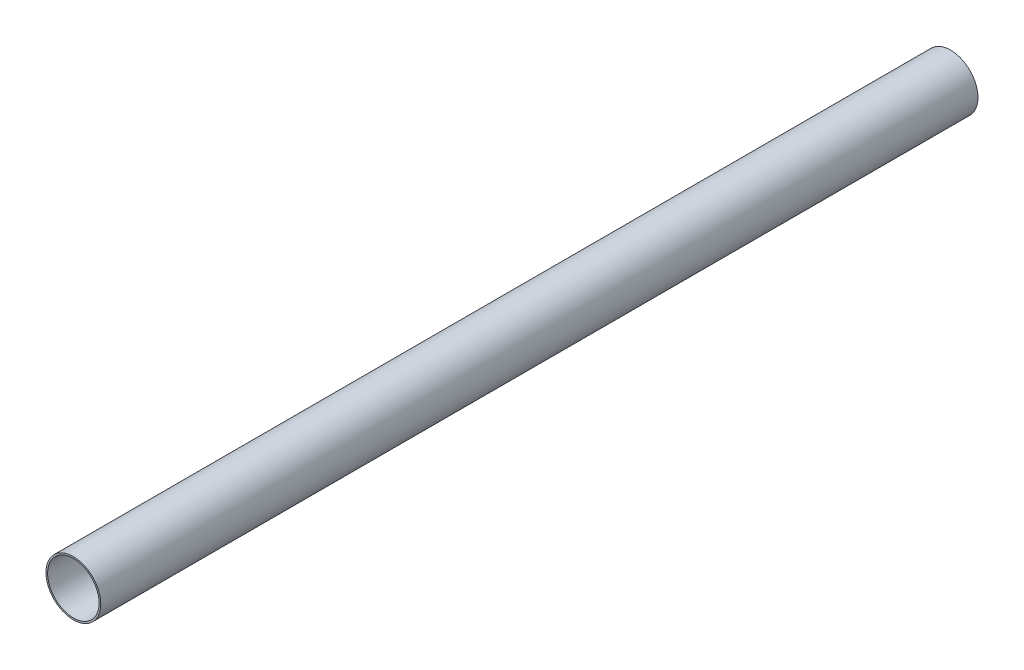
SolidWorks part; units mm, degrees
ref_plane "Front Plane" through (0, 0, 0) normal (0, 0, 1) x (1, 0, 0)
ref_plane "Top Plane" through (0, 0, 0) normal (0, 1, 0) x (1, 0, 0)
ref_plane "Right Plane" through (0, 0, 0) normal (1, 0, 0) x (0, 0, -1)
sketch "Sketch1" plane through (0, 0, 0) normal (0, 0, 1) x (1, 0, 0)
  circle A0 centre (0, 0) radius 50
  circle A1 centre (0, 0) radius 47
  dimension "D1" = 100
  dimension "D2" = 3
extrude "Boss-Extrude1" add sketch "Sketch1" along normal blind 1600
